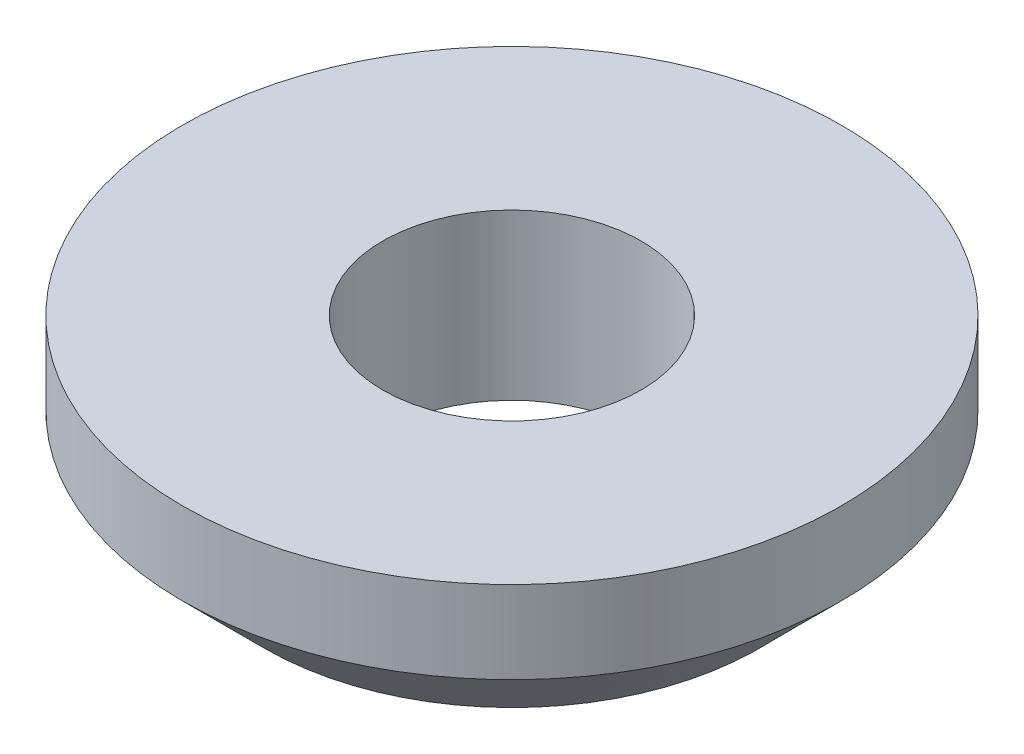
SolidWorks part; units mm, degrees
ref_plane "Front Plane" through (0, 0, 0) normal (0, 0, 1) x (1, 0, 0)
ref_plane "Top Plane" through (0, 0, 0) normal (0, 1, 0) x (1, 0, 0)
ref_plane "Right Plane" through (0, 0, 0) normal (1, 0, 0) x (0, 0, -1)
sketch "Sketch1" plane through (0, 0, 0) normal (0, 1, 0) x (1, 0, 0)
  circle A0 centre (0, 0) radius 6.35
  circle A1 centre (0, 0) radius 2.4892
  dimension "D1" = 12.7
  dimension "D2" = 4.9784
extrude "Boss-Extrude1" add sketch "Sketch1" along normal mid plane 3.175
chamfer "Chamfer1" distance 1.5875 angle 45 1 edges at (0, -1.5875, 6.35)
